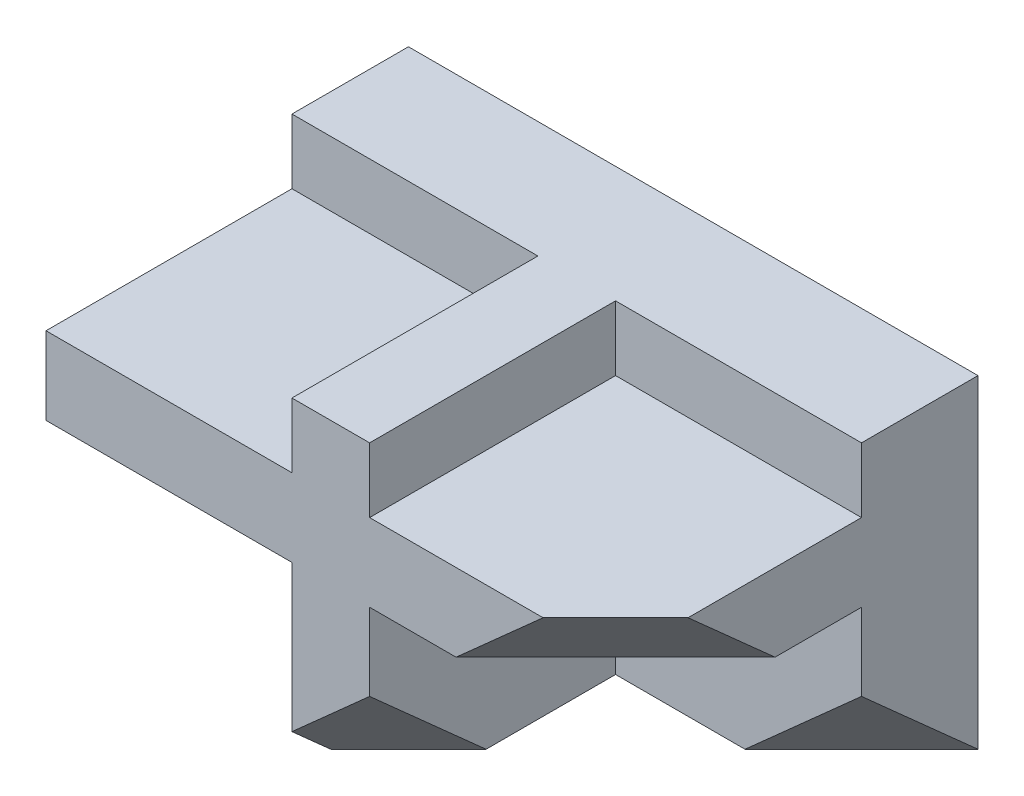
SolidWorks part; units mm, degrees
ref_plane "Front Plane" through (0, 0, 0) normal (0, 0, 1) x (1, 0, 0)
ref_plane "Top Plane" through (0, 0, 0) normal (0, 1, 0) x (1, 0, 0)
ref_plane "Right Plane" through (0, 0, 0) normal (1, 0, 0) x (0, 0, -1)
sketch "Sketch1" plane through (0, 0, 0) normal (0, 0, 1) x (1, 0, 0)
  line L1 (44, -25) -> (-44, -25)
  line L2 (44, -25) -> (44, 25)
  line L3 (44, 25) -> (-44, 25)
  line L4 (-44, -25) -> (-44, 25)
  line L5 (44, -25) -> (-44, 25) construction
  line L6 (44, 25) -> (-44, -25) construction
  point P0 (0, 0)
  dimension "D1" = 50
  dimension "D2" = 88
extrude "Boss-Extrude1" add sketch "Sketch1" along normal blind 18
sketch "Sketch2" plane through (0, 0, 18) normal (0, 0, 1) x (1, 0, 0)
  line L0 (-6, 25) -> (-6, 15)
  line L1 (44, 25) -> (-44, 25) construction
  line L2 (-6, 15) -> (-44, 15)
  line L3 (-44, 25) -> (-44, -25) construction
  line L4 (-44, 15) -> (-44, 3)
  line L5 (-44, 3) -> (-6, 3)
  line L6 (-6, 3) -> (-6, -25)
  line L7 (-44, -25) -> (44, -25) construction
  line L8 (-6, -25) -> (6, -25)
  line L9 (6, -25) -> (6, 3)
  line L10 (6, 3) -> (44, 3)
  line L11 (44, -25) -> (44, 25) construction
  line L12 (44, 3) -> (44, 15)
  line L13 (44, 15) -> (6, 15)
  line L14 (6, 15) -> (6, 25)
  line L15 (6, 25) -> (-6, 25)
extrude "Boss-Extrude2" add sketch "Sketch2" along normal blind 38
sketch "Sketch3" plane through (0, 0, 56) normal (0, 0, 1) x (1, 0, 0)
  line L1 (44, -25) -> (-44, -25) construction
  line L2 (44, -25) -> (44, 25) construction
  line L3 (44, 25) -> (-44, 25) construction
  line L4 (-44, -25) -> (-44, 25) construction
  line L5 (44, -25) -> (-44, 25) construction
  line L6 (44, 25) -> (-44, -25) construction
  point P1 (0, 0)
sketch "Sketch4" plane through (0, -25, 0) normal (0, -1, 0) x (1, 0, 0)
  line L0 (44, 0) -> (-12, 56) construction
  line L1 (44, 56) -> (-44, 56) construction
  line L2 (-44, 0) -> (44, 0) construction
  dimension "D1" = 45
ref_plane "Plane1" through (22.1239, -24.7788, 22.1239) normal (-0.5543, 0.6208, -0.5543) x (0.8323, 0.4135, -0.3692)
sketch "Sketch5" plane through (22.1239, -24.7788, 22.1239) normal (-0.5543, 0.6208, -0.5543) x (0.8323, 0.4135, -0.3692)
  line L0 (26.2839, 16.6504) -> (-40.9995, -25.1221)
  line L1 (-40.9995, -25.1221) -> (26.2839, -58.4229)
  line L2 (26.2839, -58.4229) -> (26.2839, 16.6504)
extrude "Cut-Extrude1" cut sketch "Sketch5" against normal blind 58
